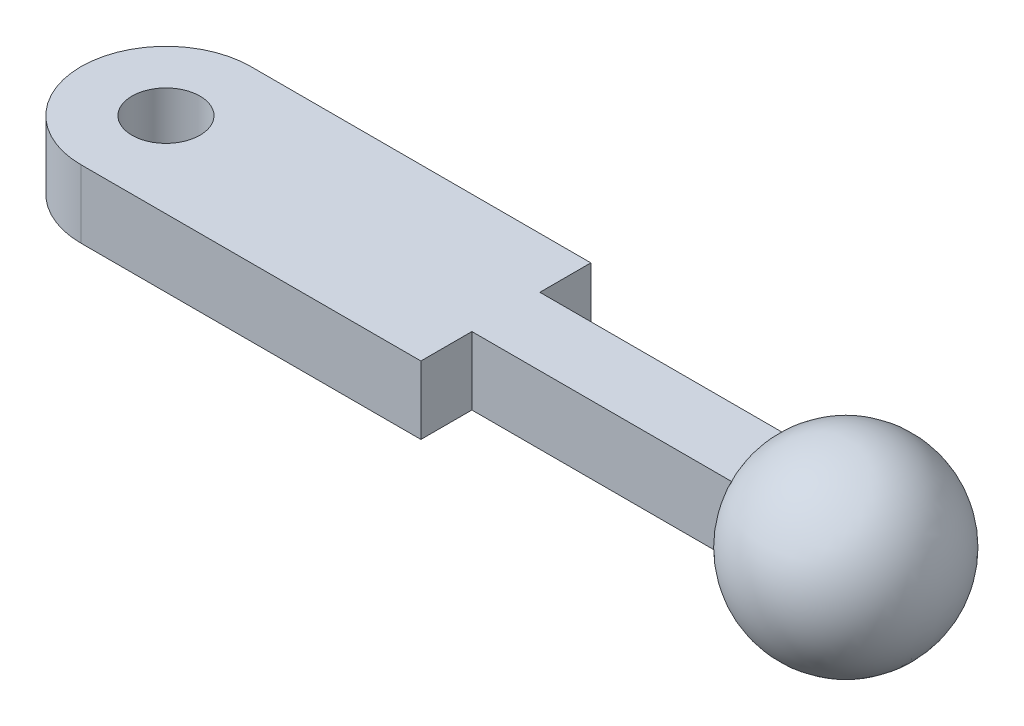
SolidWorks part; units mm, degrees
ref_plane "Front Plane" through (0, 0, 0) normal (0, 0, 1) x (1, 0, 0)
ref_plane "Top Plane" through (0, 0, 0) normal (0, 1, 0) x (1, 0, 0)
ref_plane "Right Plane" through (0, 0, 0) normal (1, 0, 0) x (0, 0, -1)
sketch "Sketch1" plane through (0, 0, 0) normal (0, 1, 0) x (1, 0, 0)
  line L0 (-10, 0) -> (0, 0) construction
  line L1 (-10, 2.5) -> (0, 2.5)
  line L2 (-10, -2.5) -> (0, -2.5)
  line L3 (0, 2.5) -> (0, -2.5)
  arc A0 (-10, 2.5) -> (-10, -2.5) centre (-10, 0) ccw
  circle A3 centre (-10, 0) radius 1
  point P3 (0, 0)
  dimension "D3" = 2
  dimension "D4" = 2.5
  dimension "D5" = 10
  dimension "D6" = 2.5
  dimension "D2" = 5
  dimension "D12" = 10
extrude "Boss-Extrude1" add sketch "Sketch1" along normal blind 2
sketch "Sketch2" plane through (0, 0, 0) normal (0, 0, 1) x (1, 0, 0)
  line L1 (0.0125, 0) -> (-0.0002, 0)
  line L5 (-10, 0) -> (0, 0) construction
  point P2 (0.0125, 1)
  dimension "D2" = 0
sketch "Sketch4" plane through (0, 0, 0) normal (1, 0, 0) x (0, 0, -1)
  line L1 (-1, 2) -> (1, 2)
  line L2 (-1, 2) -> (-1, 0)
  line L3 (-1, 0) -> (1, 0)
  line L4 (1, 2) -> (1, 0)
  line L5 (-1, 2) -> (1, 0) construction
  line L6 (-1, 0) -> (1, 2) construction
  point P0 (0, 1)
  dimension "D1" = 2
  dimension "D2" = 2
extrude "Boss-Extrude2" add sketch "Sketch4" along normal blind 11
ref_plane "Plane1" through (0, 0, 0) normal (0, 0, 1) x (1, 0, 0)
sketch "Sketch5" plane through (0, 2, 0) normal (0, 1, 0) x (1, 0, 0)
  line L2 (11, 1) -> (0, 1) construction
  line L3 (11, -1) -> (0, -1) construction
  line L4 (10, 1) -> (10, 1.5)
  line L5 (10, 1.5) -> (12, 1.5)
  line L6 (12, 1.5) -> (12, -1.5)
  line L7 (12, -1.5) -> (10, -1.5)
  line L8 (10, -1.5) -> (10, -1)
  line L9 (11, 1) -> (11, -1) construction
  arc A0 (10, 1) -> (10, -1) centre (10, 0) cw
  dimension "D1" = 1
  dimension "D2" = 3
  dimension "D3" = 0.5
  dimension "D4" = 2
extrude "Cut-Extrude1" cut sketch "Sketch5" against normal through all both
sketch "Sketch6" plane through (0, 0, -1) normal (0, 0, -1) x (-1, 0, 0)
  line L0 (-10, 0) -> (-10, 2) construction
  line L1 (-10, 2) -> (-10, 2.5)
  line L2 (-10, 2.5) -> (-12, 2.5)
  line L3 (-12, 2.5) -> (-12, -0.5)
  line L4 (-12, -0.5) -> (-10, -0.5)
  line L5 (-10, -0.5) -> (-10, 0)
  arc A0 (-10, 0) -> (-10, 2) centre (-10, 1) cw
  dimension "D1" = 0.5
  dimension "D2" = 3
  dimension "D4" = 2
  dimension "D5" = 2
extrude "Cut-Extrude2" cut sketch "Sketch6" against normal through all both
sketch "Sketch7" plane through (0, 0, -1) normal (0, 0, -1) x (-1, 0, 0)
  line L0 (-10, 0) -> (-10, 2) construction
  circle A0 centre (-10, 1) radius 0.5
extrude "Cut-Extrude3" cut sketch "Sketch7" against normal through all both
sketch "Sketch8" plane through (0, 0, 0) normal (0, 0, 1) x (1, 0, 0)
  line L0 (10, 1) -> (10, 0) construction
  line L1 (11, 1) -> (0, 1) construction
  line L2 (0, 2) -> (0, 0) construction
  arc A0 (10, 0) -> (11, 1) centre (10, 1) ccw construction
  arc A1 (11, 1) -> (10, 2) centre (10, 1) ccw construction
sketch "Sketch10" plane through (0, 0, 0) normal (0, 0, 1) x (1, 0, 0)
  line L0 (10, 1) -> (10, 3.75)
  line L1 (10, 1) -> (10, -1.75)
  arc A0 (10, 3.75) -> (10, -1.75) centre (10, 1) cw
  dimension "D1" = 2.75
  dimension "D2" = 2.75
revolve "Revolve1" add sketch "Sketch10" angle 360 about L0
